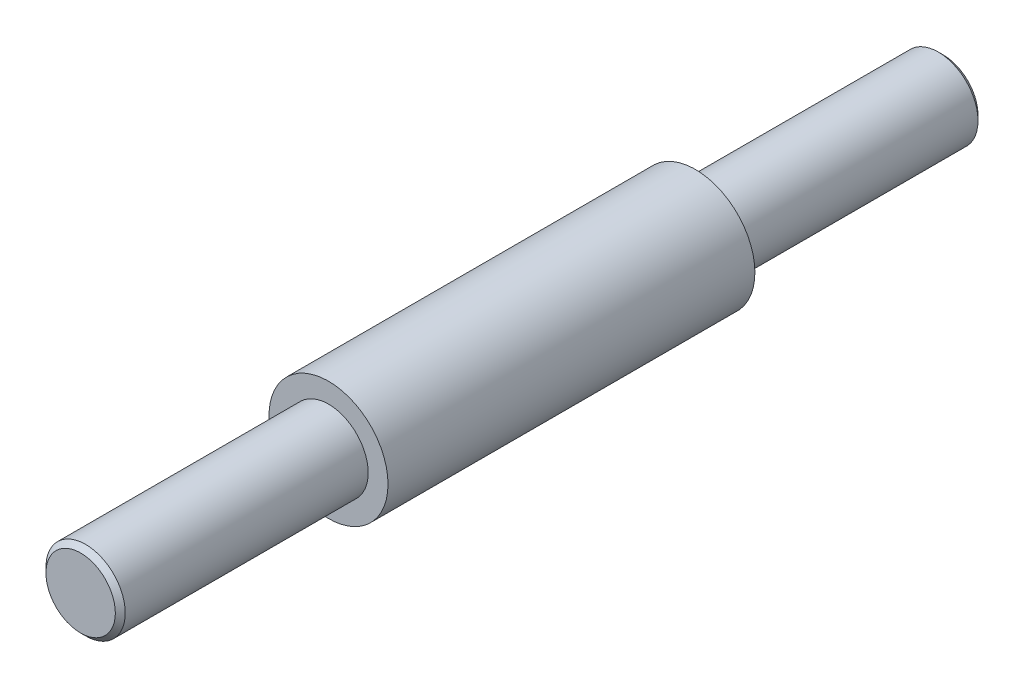
SolidWorks part; units mm, degrees
ref_plane "Piano frontale" through (0, 0, 0) normal (0, 0, 1) x (1, 0, 0)
ref_plane "Piano superiore" through (0, 0, 0) normal (0, 1, 0) x (1, 0, 0)
ref_plane "Piano destro" through (0, 0, 0) normal (1, 0, 0) x (0, 0, -1)
sketch "Schizzo1" plane through (0, 0, 0) normal (0, 0, 1) x (1, 0, 0)
  circle A0 centre (0, 0) radius 6
  dimension "D1" = 12
extrude "Estrusione1" add sketch "Schizzo1" along normal blind 37
sketch "Schizzo3" plane through (0, 0, 37) normal (0, 0, 1) x (1, 0, 0)
  circle A0 centre (0, 0) radius 4
  dimension "D1" = 8
extrude "Estrusione2" add sketch "Schizzo3" along normal blind 25
cosmetic thread "Filettatura cosmetica3" parameters "D1"=15, "D2"=6
sketch "Schizzo4" plane through (0, 0, 0) normal (0, 0, -1) x (-1, 0, 0)
  circle A0 centre (0, 0) radius 4
  dimension "D1" = 8
extrude "Estrusione3" add sketch "Schizzo4" along normal blind 25
cosmetic thread "Filettatura cosmetica2" parameters "D1"=15, "D2"=6
chamfer "Smusso1" distance 0.5 angle 45 2 edges at (-4, 0, -25) (4, 0, 62)
